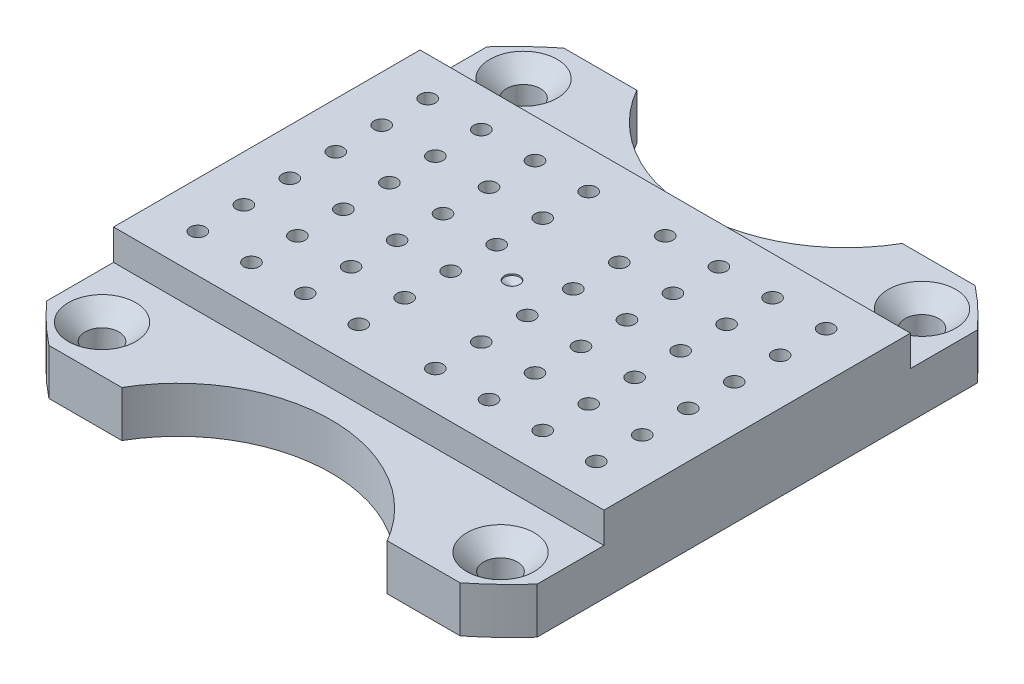
SolidWorks part; units mm, degrees
ref_plane "Front Plane" through (0, 0, 0) normal (0, 0, 1) x (1, 0, 0)
ref_plane "Top Plane" through (0, 0, 0) normal (0, 1, 0) x (1, 0, 0)
ref_plane "Right Plane" through (0, 0, 0) normal (1, 0, 0) x (0, 0, -1)
sketch "Skizze1" plane through (0, 0, 0) normal (0, 1, 0) x (1, 0, 0)
  line L1 (-16, 16.8) -> (16, 16.8)
  line L2 (-16, 16.8) -> (-16, -16.8)
  line L3 (-16, -16.8) -> (16, -16.8)
  line L4 (16, 16.8) -> (16, -16.8)
  line L5 (0, -16.8) -> (0, 16.8) construction
  line L6 (-16, 0) -> (16, 0) construction
  point P144 (0, 0)
  dimension "D1" = 32
  dimension "D2" = 33.6
extrude "Aufsatz-Linear austragen1" add sketch "Skizze1" along normal blind 5
sketch "Skizze9" plane through (0, 5, 0) normal (0, 1, 0) x (1, 0, 0)
  line L0 (0, 16.8) -> (0, -16.8) construction
  line L1 (16, 16.8) -> (-16, 16.8) construction
  line L2 (-16, -16.8) -> (16, -16.8) construction
  line L3 (-16, 0) -> (16, 0) construction
  line L4 (16, 7.5) -> (-16, 7.5) construction
  line L5 (-13, 7.5) -> (-13, -7.5) construction
  line L6 (-16, 16.8) -> (-16, -16.8) construction
  line L7 (16, -16.8) -> (16, 16.8) construction
  circle A0 centre (-13, 7.5) radius 0.5
  circle A1 centre (-9.5, 7.5) radius 0.5
  circle A2 centre (-6, 7.5) radius 0.5
  circle A3 centre (-2.5, 7.5) radius 0.5
  circle A4 centre (-2.5, 4.5) radius 0.5
  circle A5 centre (13, -7.5) radius 0.5
  circle A6 centre (13, -4.5) radius 0.5
  circle A7 centre (13, -1.5) radius 0.5
  circle A8 centre (13, 1.5) radius 0.5
  circle A9 centre (13, 4.5) radius 0.5
  circle A10 centre (-2.5, 1.5) radius 0.5
  circle A11 centre (-9.5, 4.5) radius 0.5
  circle A12 centre (-6, 4.5) radius 0.5
  circle A13 centre (-2.5, -1.5) radius 0.5
  circle A14 centre (-2.5, -4.5) radius 0.5
  circle A15 centre (-2.5, -7.5) radius 0.5
  circle A16 centre (6, -7.5) radius 0.5
  circle A17 centre (9.5, -7.5) radius 0.5
  circle A18 centre (2.5, -7.5) radius 0.5
  circle A19 centre (2.5, -4.5) radius 0.5
  circle A20 centre (6, -4.5) radius 0.5
  circle A21 centre (-9.5, 1.5) radius 0.5
  circle A22 centre (-6, 1.5) radius 0.5
  circle A23 centre (2.5, -1.5) radius 0.5
  circle A24 centre (2.5, 1.5) radius 0.5
  circle A25 centre (9.5, -4.5) radius 0.5
  circle A26 centre (2.5, 4.5) radius 0.5
  circle A27 centre (2.5, 7.5) radius 0.5
  circle A28 centre (6, -1.5) radius 0.5
  circle A29 centre (9.5, -1.5) radius 0.5
  circle A31 centre (-9.5, -1.5) radius 0.5
  circle A32 centre (-6, -1.5) radius 0.5
  circle A36 centre (6, 1.5) radius 0.5
  circle A37 centre (9.5, 1.5) radius 0.5
  circle A40 centre (6, 4.5) radius 0.5
  circle A41 centre (-9.5, -4.5) radius 0.5
  circle A42 centre (-6, -4.5) radius 0.5
  circle A45 centre (9.5, 4.5) radius 0.5
  circle A48 centre (6, 7.5) radius 0.5
  circle A49 centre (9.5, 7.5) radius 0.5
  circle A50 centre (13, 7.5) radius 0.5
  circle A51 centre (-9.5, -7.5) radius 0.5
  circle A52 centre (-6, -7.5) radius 0.5
  circle A122 centre (-13, 4.5) radius 0.5
  circle A123 centre (-13, 1.5) radius 0.5
  circle A124 centre (-13, -1.5) radius 0.5
  circle A125 centre (-13, -4.5) radius 0.5
  circle A126 centre (-13, -7.5) radius 0.5
  dimension "D1" = 1
  dimension "D3" = 3
  dimension "D4" = 4
  dimension "D6" = 3.5
  dimension "D7" = 3
  dimension "D2" = 7.5
  dimension "D5" = 6
extrude "Schnitt-Linear austragen1" cut sketch "Skizze9" against normal blind 6
sketch "Skizze10" plane through (0, 5, 0) normal (0, 1, 0) x (1, 0, 0)
  line L0 (16, -16.8) -> (16, 16.8) construction
  line L1 (-16, 16.8) -> (16, 16.8)
  line L2 (-16, 16.8) -> (-16, 10)
  line L3 (-16, 10) -> (16, 10)
  line L4 (16, 16.8) -> (16, 10)
  line L5 (0, 10) -> (0, 16.8) construction
  line L6 (-16, 13.4) -> (16, 13.4) construction
  line L7 (-16, 16.8) -> (-16, -16.8) construction
  line L8 (16, -16.8) -> (-16, -16.8)
  line L9 (16, -16.8) -> (16, -10)
  line L10 (16, -10) -> (-16, -10)
  line L11 (-16, -16.8) -> (-16, -10)
  line L12 (0, -10) -> (0, -16.8) construction
  line L13 (16, -13.4) -> (-16, -13.4) construction
  line L14 (-16, 0) -> (16, 0) construction
  point P162 (0, -13.4)
  point P184 (0, 13.4)
  dimension "D1" = 20
extrude "Schnitt-Linear austragen2" cut sketch "Skizze10" against normal blind 2
hole_wizard "Formsenkung für M2 Linsensenkschraube mit Schlitz2" positions "Skizze11" profile "Skizze12" countersink size "M2" standard "DIN"
sketch "Skizze11" plane through (0, 3, 0) normal (0, 1, 0) x (1, 0, 0)
  line L1 (0, 16.8) -> (0, -16.8) construction
  line L2 (16, 16.8) -> (-16, 16.8) construction
  line L3 (-16, -16.8) -> (16, -16.8) construction
  line L6 (17.5226, 0) -> (-16, 0) construction
  line L8 (-16, 10) -> (-16, -10) construction
  point P0 (-13, 13.75)
  point P19 (13, 13.75)
  point P20 (13, -13.75)
  point P21 (-13, -13.75)
  dimension "D1" = 27.5
  dimension "D2" = 26
sketch "Skizze12" plane through (-13, 3, -13.75) normal (1, 0, 0) x (0, 0, 1)
  line L0 (0, 0) -> (0, 4.6609)
  line L1 (0, 4.6609) -> (1.1, 4)
  line L2 (1.1, 4) -> (1.1, 1.1)
  line L3 (1.1, 1.1) -> (2.2, 0)
  line L5 (2.2, 0) -> (0, 0)
  line L6 (-1.1, 1.1) -> (-2.2, 0) construction
  line L10 (0, 4.6609) -> (-1.1, 4) construction
  line L11 (0, -6.35) -> (0, 107.95) construction
  dimension "Bohrerdurchmesser" = 2.2
  dimension "Bohrungstiefe" = 4
  dimension "Senkdurchmesser (Oben)" = 4.4
  dimension "Senkwinkel (Oben)" = 90
  dimension "Spitzenwinkel" = 118
sketch "Skizze13" plane through (0, 3, 0) normal (0, 1, 0) x (1, 0, 0)
  line L1 (0, -16.8) -> (0, 16.8) construction
  line L2 (-16, -16.8) -> (16, -16.8) construction
  line L3 (16, 16.8) -> (-16, 16.8) construction
  circle A0 centre (0, 21.8) radius 10
  dimension "D1" = 20
  dimension "D2" = 5
extrude "Schnitt-Linear austragen3" cut sketch "Skizze13" against normal through all
mirror "Spiegeln3" about plane through (0, 0, 0) normal (0, 0, 1) of "Schnitt-Linear austragen3"
sketch "Skizze14" plane through (0, 5, 0) normal (0, 1, 0) x (1, 0, 0)
  circle A0 centre (0, 0) radius 21.5
  dimension "D1" = 43
extrude "Schnitt-Linear-Austragen-Dünn1" cut sketch "Skizze14" against normal blind 10 thin
hole_wizard "Ø1.0 (1) Durchmesser Bohrung1" positions "Skizze15" profile "Skizze16" hole size "Ø1.0" standard "DIN"
sketch "Skizze15" plane through (0, 5, 0) normal (0, 1, 0) x (1, 0, 0)
  point P0 (0, 0)
sketch "Skizze16" plane through (0, 5, 0) normal (1, 0, 0) x (0, 0, 1)
  line L0 (0, 0) -> (0, 0.4004)
  line L1 (0, 0.4004) -> (0.5, 0.1)
  line L2 (0.5, 0.1) -> (0.5, 0)
  line L5 (0.5, 0) -> (0, 0)
  line L10 (0, 0.4004) -> (-0.5, 0.1) construction
  line L11 (0, -6.35) -> (0, 107.95) construction
  dimension "Bohrerdurchmesser" = 1
  dimension "Bohrungstiefe" = 0.1
  dimension "Spitzenwinkel" = 118
